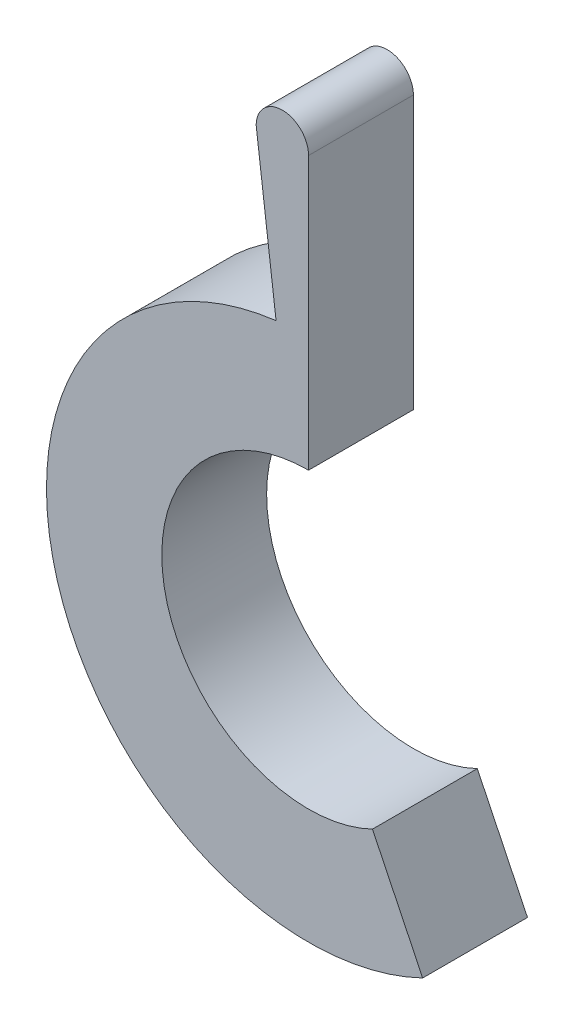
SolidWorks part; units mm, degrees
ref_plane "Plano frontal" through (0, 0, 0) normal (0, 0, 1) x (1, 0, 0)
ref_plane "Plano superior" through (0, 0, 0) normal (0, 1, 0) x (1, 0, 0)
ref_plane "Plano direito" through (0, 0, 0) normal (1, 0, 0) x (0, 0, -1)
sketch "Esboço1" plane through (0, 0, 0) normal (0, 0, 1) x (1, 0, 0)
  line L0 (0, 0) -> (10, 0) construction
  line L1 (0, 0) -> (-10, 0) construction
  line L2 (-10, 0) -> (-10, -9.798) construction
  line L6 (0, 20) -> (0, 40)
  line L7 (-5, 40) -> (-3.1009, 24.8069)
  line L8 (6.0951, -12.6035) -> (10.8842, -22.5063)
  line L9 (0, 20) -> (0, 14)
  arc A2 (0, 25) -> (-3.1009, 24.8069) centre (0, 0) ccw construction
  arc A3 (0, 40) -> (-4.9231, 39.3846) centre (-2.5, 40) ccw
  arc A4 (-3.1009, 24.8069) -> (10.8842, -22.5063) centre (0, 0) ccw
  arc A5 (0, 14) -> (6.0951, -12.6035) centre (0, 0) ccw
  dimension "D1" = 50
  dimension "D2" = 20
  dimension "D3" = 10
  dimension "D4" = 5
extrude "Ressalto-extrusão1" add sketch "Esboço1" along normal blind 10
